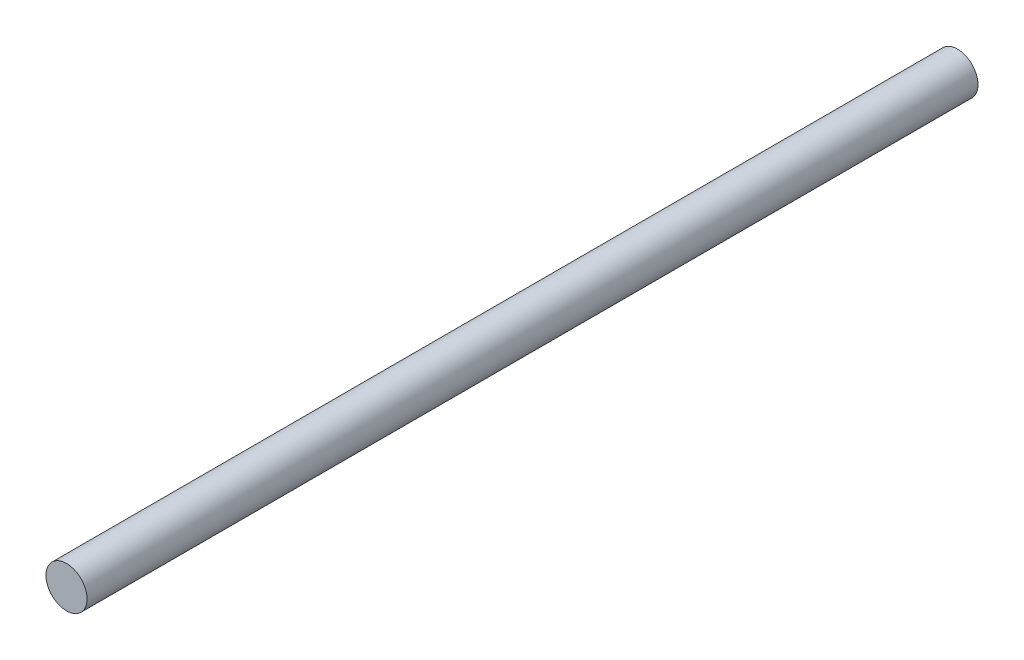
SolidWorks part; units mm, degrees
ref_plane "Front Plane" through (0, 0, 0) normal (0, 0, 1) x (1, 0, 0)
ref_plane "Top Plane" through (0, 0, 0) normal (0, 1, 0) x (1, 0, 0)
ref_plane "Right Plane" through (0, 0, 0) normal (1, 0, 0) x (0, 0, -1)
sketch "Sketch1" plane through (0, 0, 0) normal (0, 0, 1) x (1, 0, 0)
  circle A0 centre (0, 0) radius 2.375
  dimension "D1" = 4.75
extrude "Boss-Extrude1" add sketch "Sketch1" along normal blind 103
